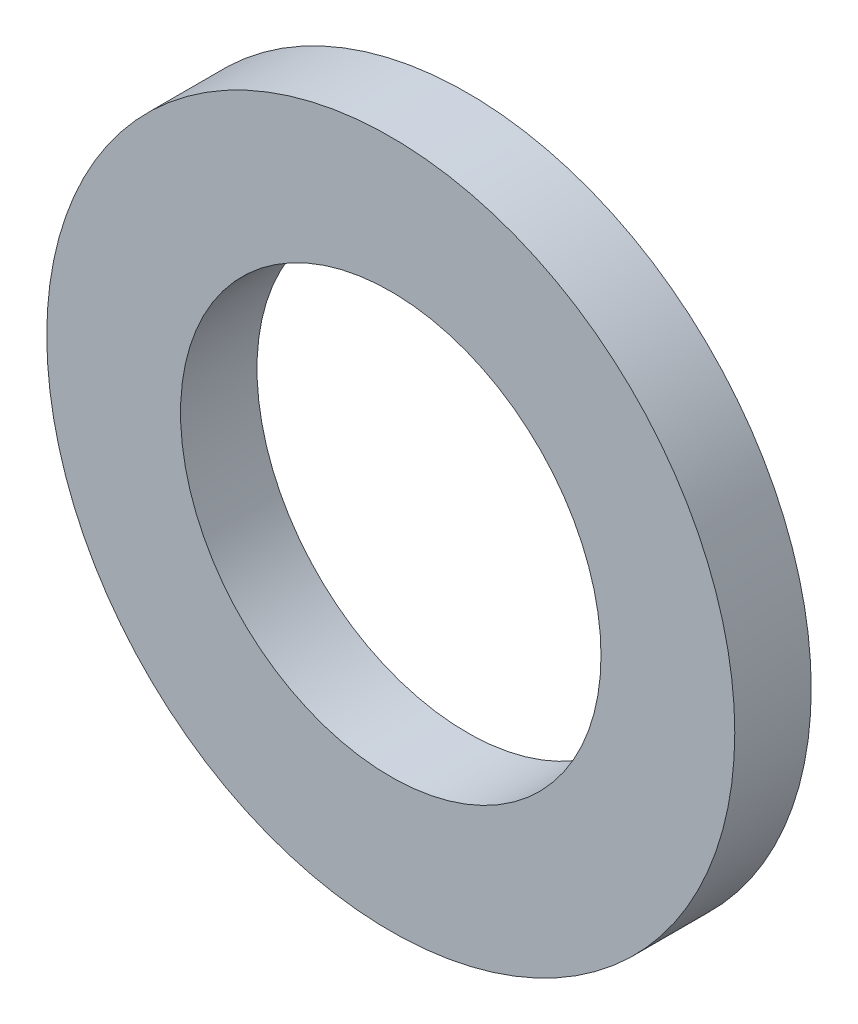
SolidWorks part; units mm, degrees
ref_plane "Alzado" through (0, 0, 0) normal (0, 0, 1) x (1, 0, 0)
ref_plane "Planta" through (0, 0, 0) normal (0, 1, 0) x (1, 0, 0)
ref_plane "Vista lateral" through (0, 0, 0) normal (1, 0, 0) x (0, 0, -1)
sketch "Croquis1" plane through (0, 0, 0) normal (0, 0, 1) x (1, 0, 0)
  circle A0 centre (0, 0) radius 2.75
  circle A1 centre (0, 0) radius 4.5
  dimension "D1" = 5.5
  dimension "D2" = 9
extrude "Saliente-Extruir1" add sketch "Croquis1" against normal blind 1
